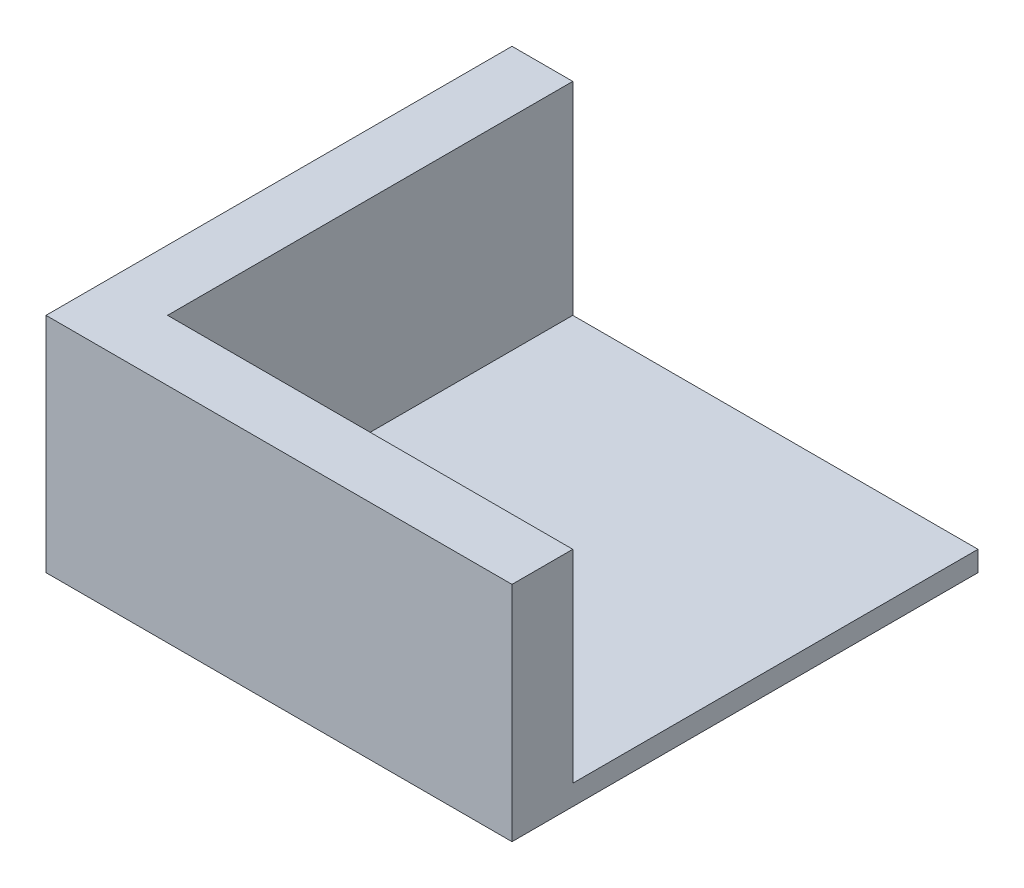
SolidWorks part; units mm, degrees
ref_plane "Front Plane" through (0, 0, 0) normal (0, 0, 1) x (1, 0, 0)
ref_plane "Top Plane" through (0, 0, 0) normal (0, 1, 0) x (1, 0, 0)
ref_plane "Right Plane" through (0, 0, 0) normal (1, 0, 0) x (0, 0, -1)
sketch "Sketch1" plane through (0, 0, 0) normal (0, 1, 0) x (1, 0, 0)
  line L0 (-36.4899, 17.7501) -> (-36.4899, -2.2499)
  line L1 (-36.4899, -2.2499) -> (-13.4899, -2.2499)
  line L2 (-13.4899, -2.2499) -> (-13.4899, 0.7501)
  line L3 (-13.4899, 0.7501) -> (-33.4899, 0.7501)
  line L4 (-33.4899, 0.7501) -> (-33.4899, 20.7501)
  line L5 (-33.4899, 20.7501) -> (-36.4899, 20.7501)
  line L6 (-36.4899, 20.7501) -> (-36.4899, 17.7501)
  dimension "D1" = 20
  dimension "D2" = 23
  dimension "D3" = 3
  dimension "D4" = 20
  dimension "D5" = 20
extrude "Boss-Extrude1" add sketch "Sketch1" along normal blind 10
sketch "Sketch2" plane through (0, 0, 0) normal (0, -1, 0) x (1, 0, 0)
  line L1 (-36.4899, 2.2499) -> (-13.4899, 2.2499)
  line L2 (-36.4899, 2.2499) -> (-36.4899, -20.7501)
  line L3 (-36.4899, -20.7501) -> (-13.4899, -20.7501)
  line L4 (-13.4899, 2.2499) -> (-13.4899, -20.7501)
  dimension "D1" = 23
extrude "Boss-Extrude2" add sketch "Sketch2" along normal blind 1
